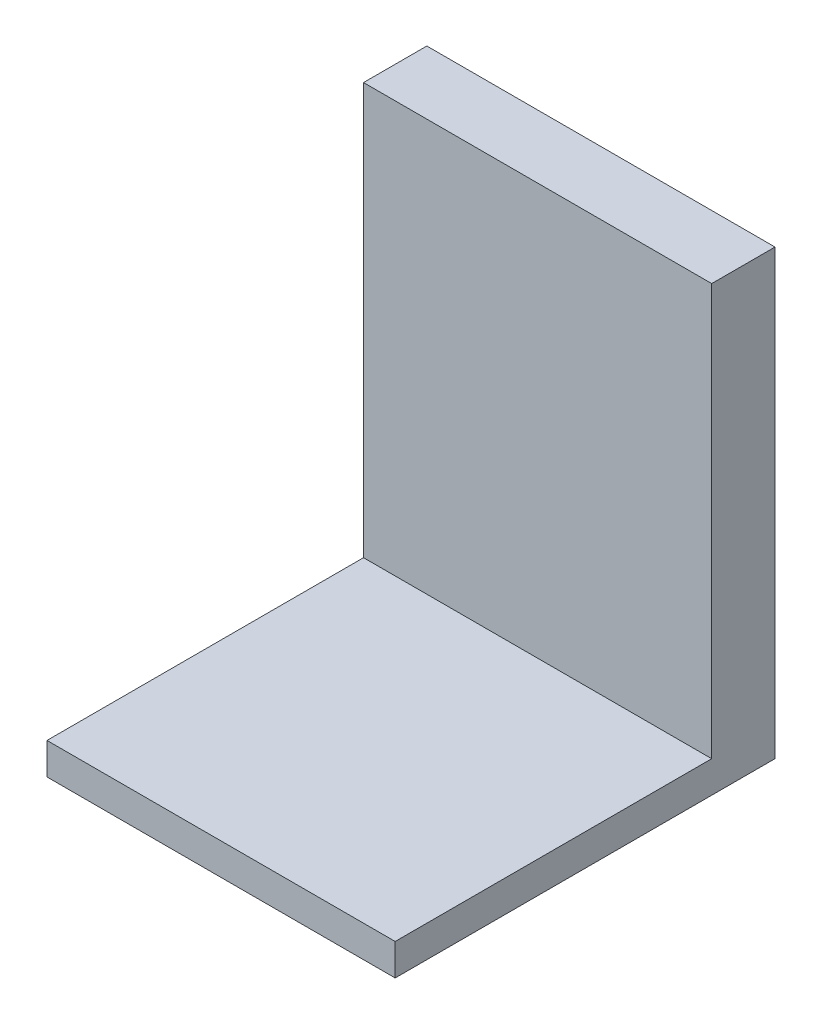
SolidWorks part; units mm, degrees
ref_plane "정면" through (0, 0, 0) normal (0, 0, 1) x (1, 0, 0)
ref_plane "윗면" through (0, 0, 0) normal (0, 1, 0) x (1, 0, 0)
ref_plane "우측면" through (0, 0, 0) normal (1, 0, 0) x (0, 0, -1)
sketch "Sketch1" plane through (0, 0, 0) normal (0, 1, 0) x (1, 0, 0)
  line L1 (0, 0) -> (670, 0)
  line L2 (0, 0) -> (0, 120)
  line L3 (0, 120) -> (670, 120)
  line L4 (670, 0) -> (670, 120)
  dimension "700" = 670
  dimension "D2" = 120
extrude "Boss-Extrude1" add sketch "Sketch1" along normal blind 530
sketch "Sketch2" plane through (0, 0, 0) normal (0, 0, 1) x (1, 0, 0)
  line L0 (0, 530) -> (0, 0) construction
  line L1 (10, 280) -> (110, 280)
  line L2 (10, 280) -> (10, 480)
  line L3 (10, 480) -> (110, 480)
  line L4 (110, 280) -> (110, 480)
  line L5 (0, 0) -> (670, 0) construction
  line L6 (120, 280) -> (120, 480)
  line L7 (120, 280) -> (220, 280)
  line L8 (220, 280) -> (220, 480)
  line L9 (120, 480) -> (220, 480)
  line L10 (230, 280) -> (230, 480)
  line L11 (230, 280) -> (330, 280)
  line L12 (330, 280) -> (330, 480)
  line L13 (230, 480) -> (330, 480)
  line L14 (340, 280) -> (340, 480)
  line L15 (340, 280) -> (440, 280)
  line L16 (440, 280) -> (440, 480)
  line L17 (340, 480) -> (440, 480)
  line L18 (450, 280) -> (450, 480)
  line L19 (450, 280) -> (550, 280)
  line L20 (550, 280) -> (550, 480)
  line L21 (450, 480) -> (550, 480)
  line L22 (560, 280) -> (560, 480)
  line L23 (560, 280) -> (660, 280)
  line L24 (660, 280) -> (660, 480)
  line L25 (560, 480) -> (660, 480)
  line L27 (10, 10) -> (660, 10)
  line L28 (10, 10) -> (10, 260)
  line L29 (10, 260) -> (660, 260)
  line L30 (660, 10) -> (660, 260)
  line L31 (0, 530) -> (670, 530) construction
  point P6 (10, 380)
  dimension "D1" = 100
  dimension "D2" = 200
  dimension "D3" = 10
  dimension "D4" = 50
  dimension "D6" = 10
  dimension "D7" = 20
  dimension "D5" = 6
extrude "Cut-Extrude1" cut sketch "Sketch2" against normal blind 100
sketch "Sketch3" plane through (0, 530, 0) normal (0, 1, 0) x (1, 0, 0)
  line L1 (670, 120) -> (0, 120) construction
  line L2 (0, 120) -> (0, 0) construction
  circle A0 centre (60, 60) radius 50
  circle A1 centre (170, 60) radius 50
  circle A2 centre (280, 60) radius 50
  circle A3 centre (390, 60) radius 50
  circle A4 centre (500, 60) radius 50
  circle A5 centre (610, 60) radius 50
  dimension "D1" = 100
  dimension "D2" = 10
  dimension "D3" = 10
  dimension "D4" = 6
extrude "Cut-Extrude2" cut sketch "Sketch3" against normal blind 260
hole_wizard "Ø12.0 (12) Diameter Hole2" positions "3DSketch1" profile "Sketch7" hole size "Ø12.0" standard "Ansi Metric"
sketch3d "3DSketch1"
  point P0 (59.7046, 270, -102.4117)
  point P2 (171.5567, 270, -102.6076)
  point P4 (280.8723, 270, -102.3969)
  point P6 (391.0687, 270, -102.7535)
  point P8 (500.7133, 270, -101.754)
  point P10 (609.5165, 270, -101.1227)
sketch "Sketch7" plane through (59.7046, 270, -102.4117) normal (1, 0, 0) x (0, 0, 1)
  line L0 (0, 0) -> (0, 33.6052)
  line L1 (0, 33.6052) -> (6, 30)
  line L2 (6, 30) -> (6, 0)
  line L5 (6, 0) -> (0, 0)
  line L10 (0, 33.6052) -> (-6, 30) construction
  line L11 (0, -6.35) -> (0, 107.95) construction
  dimension "구멍 지름" = 12
  dimension "구멍 깊이" = 30
  dimension "드릴 각도" = 118
sketch "Sketch8" plane through (0, 0, 0) normal (0, 0, 1) x (1, 0, 0)
  line L0 (660, 280) -> (660, 480) construction
  line L1 (10, 280) -> (660, 280)
  line L2 (10, 280) -> (10, 330)
  line L3 (10, 330) -> (660, 330)
  line L4 (660, 280) -> (660, 330)
  dimension "D1" = 50
extrude "Boss-Extrude2" add sketch "Sketch8" against normal blind 5
sketch "Sketch9" plane through (670, 0, 0) normal (1, 0, 0) x (0, 0, -1)
  line L0 (0, 530) -> (0, 0) construction
  line L1 (10, 10) -> (20, 10)
  line L2 (10, 10) -> (10, 260)
  line L3 (10, 260) -> (20, 260)
  line L4 (20, 10) -> (20, 260)
  line L5 (0, 0) -> (120, 0) construction
  dimension "D1" = 10
  dimension "D2" = 10
  dimension "D3" = 10
  dimension "D4" = 250
extrude "Cut-Extrude3" cut sketch "Sketch9" against normal blind 717
sketch "Sketch10" plane through (0, 10, 0) normal (0, 1, 0) x (1, 0, 0)
  line L0 (670, 120) -> (0, 120) construction
  line L1 (365, 61.9436) -> (350, 87.9243)
  line L2 (350, 87.9243) -> (320, 87.9243)
  line L3 (320, 87.9243) -> (305, 61.9436)
  line L4 (305, 61.9436) -> (320, 35.9628)
  line L5 (320, 35.9628) -> (350, 35.9628)
  line L6 (350, 35.9628) -> (365, 61.9436)
  line L7 (0, 120) -> (0, 0) construction
  circle A0 centre (335, 61.9436) radius 25.9808 construction
  dimension "D1" = 60
  dimension "D2" = 305
extrude "Cut-Extrude4" cut sketch "Sketch10" against normal blind 5
sketch "Sketch11" plane through (0, 0, -100) normal (0, 0, 1) x (1, 0, 0)
  line L0 (10, 10) -> (660, 10) construction
  line L1 (250, 10) -> (260, 10)
  line L2 (250, 10) -> (250, 110)
  line L3 (250, 110) -> (260, 110)
  line L4 (260, 10) -> (260, 110)
  line L5 (660, 10) -> (660, 260) construction
  line L6 (410, 10) -> (420, 10)
  line L7 (410, 10) -> (410, 110)
  line L8 (410, 110) -> (420, 110)
  line L9 (420, 10) -> (420, 110)
  line L10 (25, 198.4569) -> (325, 145.5588)
  line L11 (325, 145.5588) -> (325, 122.0178)
  line L12 (325, 122.0178) -> (345, 122.0178)
  line L13 (345, 122.0178) -> (345, 145.5588)
  line L14 (345, 145.5588) -> (645, 198.4569)
  line L15 (645, 198.4569) -> (25, 198.4569)
  point P18 (345, 133.7883)
  dimension "D1" = 10
  dimension "D2" = 10
  dimension "D3" = 100
  dimension "D4" = 100
  dimension "D5" = 150
  dimension "D6" = 240
  dimension "D7" = 20
  dimension "D8" = 65
  dimension "D9" = 100
  dimension "D10" = 620
  dimension "D11" = 100
extrude "Boss-Extrude3" add sketch "Sketch11" along normal blind 78 separate body
sketch "Sketch12" plane through (0, 0, -100) normal (0, 0, 1) x (1, 0, 0)
  line L0 (660, 260) -> (10, 260) construction
  line L1 (75.1986, 260) -> (95.1986, 260)
  line L2 (75.1986, 260) -> (75.1986, 230)
  line L3 (75.1986, 230) -> (95.1986, 230)
  line L4 (95.1986, 260) -> (95.1986, 230)
  line L5 (65.1986, 260) -> (65.1986, 240) construction
  line L6 (185.1986, 260) -> (185.1986, 230)
  line L7 (185.1986, 260) -> (205.1986, 260)
  line L8 (205.1986, 260) -> (205.1986, 230)
  line L9 (185.1986, 230) -> (205.1986, 230)
  line L10 (295.1986, 260) -> (295.1986, 230)
  line L11 (295.1986, 260) -> (315.1986, 260)
  line L12 (315.1986, 260) -> (315.1986, 230)
  line L13 (295.1986, 230) -> (315.1986, 230)
  line L14 (405.1986, 260) -> (405.1986, 230)
  line L15 (405.1986, 260) -> (425.1986, 260)
  line L16 (425.1986, 260) -> (425.1986, 230)
  line L17 (405.1986, 230) -> (425.1986, 230)
  line L18 (515.1986, 260) -> (515.1986, 230)
  line L19 (515.1986, 260) -> (535.1986, 260)
  line L20 (535.1986, 260) -> (535.1986, 230)
  line L21 (515.1986, 230) -> (535.1986, 230)
  line L22 (625.1986, 260) -> (625.1986, 230)
  line L23 (625.1986, 260) -> (645.1986, 260)
  line L24 (645.1986, 260) -> (645.1986, 230)
  line L25 (625.1986, 230) -> (645.1986, 230)
  dimension "D1" = 20
  dimension "D2" = 30
  dimension "D3" = 10
  dimension "D4" = 6
extrude "Cut-Extrude5" cut sketch "Sketch12" against normal blind 80
sketch "Sketch15" plane through (345, 0, 0) normal (1, 0, 0) x (0, 0, -1)
  line L0 (20, 10) -> (20, 260) construction
  line L1 (20, 121.4638) -> (50, 121.4638)
  line L2 (20, 121.4638) -> (20, 145)
  line L3 (20, 145) -> (50, 145)
  line L4 (50, 121.4638) -> (50, 145)
  line L5 (120, 530) -> (120, 0) construction
  line L6 (100, 116.0134) -> (70, 116.0134)
  line L7 (100, 116.0134) -> (100, 145)
  line L8 (100, 145) -> (70, 145)
  line L9 (70, 116.0134) -> (70, 145)
  line L10 (20, 260) -> (10, 260) construction
  dimension "D1" = 20
  dimension "D2" = 20
  dimension "D3" = 115
  dimension "D4" = 30
extrude "Cut-Extrude7" cut sketch "Sketch15" against normal blind 35
shell "Shell1" thickness 3
sketch "Sketch16" plane through (0, 122.0178, 0) normal (0, -1, 0) x (1, 0, 0)
  line L0 (345, -50) -> (325, -50) construction
  line L1 (328, -53) -> (342, -53)
  line L2 (328, -53) -> (328, -67)
  line L3 (328, -67) -> (342, -67)
  line L4 (342, -53) -> (342, -67)
  line L5 (325, -50) -> (325, -70) construction
  line L6 (345, -50) -> (345, -70) construction
  line L7 (325, -70) -> (345, -70) construction
  dimension "D1" = 3
  dimension "D2" = 3
  dimension "D3" = 3
  dimension "D4" = 3
extrude "Cut-Extrude8" cut sketch "Sketch16" against normal blind 35
sketch "Sketch17" plane through (0, 0, 0) normal (0, 0, 1) x (1, 0, 0)
  text T0 "<b>DIFF_USER</b>" font "Britannic Bold" height in points 72
extrude "Boss-Extrude4" add sketch "Sketch17" along normal blind 5
sketch "Sketch18" plane through (0, 0, 0) normal (0, 0, 1) x (1, 0, 0)
  line L0 (0, 530) -> (670, 530) construction
  line L1 (0, 530) -> (670, 530)
  line L2 (0, 530) -> (0, 280)
  line L3 (0, 280) -> (670, 280)
  line L4 (670, 530) -> (670, 280)
  line L5 (670, 530) -> (670, 0) construction
  line L6 (0, 0) -> (670, 0) construction
  dimension "D1" = 280
extrude "Cut-Extrude10" cut sketch "Sketch18" against normal through all both and the other way through all
delete or keep bodies "Body-Delete/Keep 2" type delete bodies bodies 109 115 112
sketch "Sketch19" plane through (0, 0, -120) normal (0, 0, -1) x (-1, 0, 0)
  line L0 (0, 280) -> (-670, 280) construction
  line L1 (0, 0) -> (-448, 0)
  line L2 (0, 0) -> (0, 280)
  line L3 (0, 280) -> (-448, 280)
  line L4 (-448, 0) -> (-448, 280)
  line L6 (-670, 0) -> (-558, 0)
  line L7 (-670, 0) -> (-670, 280)
  line L8 (-670, 280) -> (-558, 280)
  line L9 (-558, 0) -> (-558, 280)
  dimension "D1" = 110
  dimension "D2" = 448
extrude "Cut-Extrude11" cut sketch "Sketch19" against normal through all both and the other way through all
sketch "Sketch20" plane through (0, 0, -100) normal (0, 0, 1) x (1, 0, 0)
  line L0 (558, 10) -> (558, 260) construction
  line L1 (448, 280) -> (558, 280)
  line L2 (448, 280) -> (448, 140)
  line L3 (448, 140) -> (558, 140)
  line L4 (558, 280) -> (558, 140)
  dimension "D1" = 140
extrude "Cut-Extrude12" cut sketch "Sketch20" against normal through all both and the other way through all
